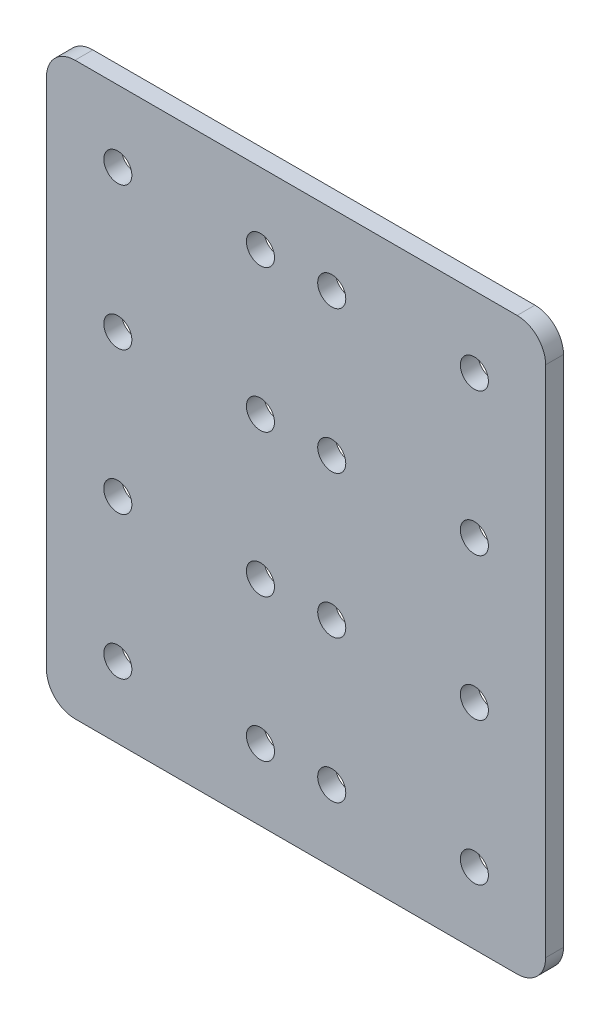
SolidWorks part; units mm, degrees
ref_plane "Front Plane" through (0, 0, 0) normal (0, 0, 1) x (1, 0, 0)
ref_plane "Top Plane" through (0, 0, 0) normal (0, 1, 0) x (1, 0, 0)
ref_plane "Right Plane" through (0, 0, 0) normal (1, 0, 0) x (0, 0, -1)
sketch "Sketch1" plane through (0, 0, 0) normal (0, 0, 1) x (1, 0, 0)
  line L0 (1136.65, 25.4) -> (1136.65, -76.2) construction
  line L1 (1176.02, 25.4) -> (1097.28, 25.4)
  line L2 (1181.1, 20.32) -> (1181.1, -71.12)
  line L3 (1176.02, -76.2) -> (1097.28, -76.2)
  line L4 (1092.2, 20.32) -> (1092.2, -71.12)
  circle A0 centre (1143, 12.7) radius 2.5
  circle A2 centre (1168.4, 12.7) radius 2.5
  circle A4 centre (1168.4, -12.7) radius 2.5
  circle A6 centre (1168.4, -38.1) radius 2.5
  circle A8 centre (1168.4, -63.5) radius 2.5
  circle A15 centre (1143, -12.7) radius 2.5
  circle A16 centre (1143, -38.1) radius 2.5
  circle A17 centre (1143, -63.5) radius 2.5
  arc A21 (1176.02, 25.4) -> (1181.1, 20.32) centre (1176.02, 20.32) cw
  arc A22 (1181.1, -71.12) -> (1176.02, -76.2) centre (1176.02, -71.12) cw
  arc A23 (1097.28, -76.2) -> (1092.2, -71.12) centre (1097.28, -71.12) cw
  arc A24 (1097.28, 25.4) -> (1092.2, 20.32) centre (1097.28, 20.32) ccw
  circle A25 centre (1155.7, 12.7) radius 2.5 [skipped]
  circle A26 centre (1155.7, -12.7) radius 2.5 [skipped]
  circle A27 centre (1155.7, -38.1) radius 2.5 [skipped]
  circle A28 centre (1155.7, -63.5) radius 2.5 [skipped]
  circle A29 centre (1104.9, 12.7) radius 2.5
  circle A30 centre (1104.9, -12.7) radius 2.5
  circle A31 centre (1104.9, -38.1) radius 2.5
  circle A32 centre (1104.9, -63.5) radius 2.5
  circle A33 centre (1130.3, -63.5) radius 2.5
  circle A34 centre (1130.3, -38.1) radius 2.5
  circle A35 centre (1130.3, -12.7) radius 2.5
  circle A36 centre (1130.3, 12.7) radius 2.5
  point P51 (1181.1, 25.4)
  point P56 (1092.2, -76.2)
  dimension "D3" = 5.08
  dimension "D1" = 3
  dimension "D2" = 4
extrude "Boss-Extrude1" add sketch "Sketch1" along normal blind 3.175
